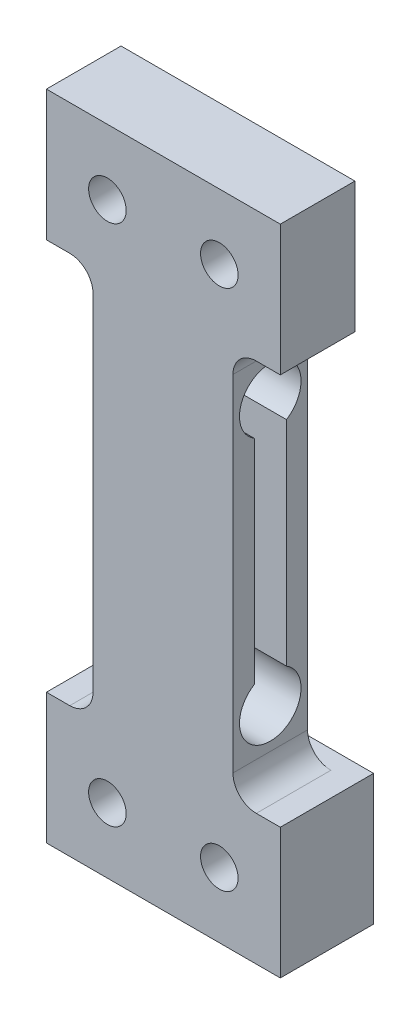
SolidWorks part; units mm, degrees
material "2024 Alloy (SN)"
ref_plane "Front Plane" through (0, 0, 0) normal (0, 0, 1) x (1, 0, 0)
ref_plane "Top Plane" through (0, 0, 0) normal (0, 1, 0) x (1, 0, 0)
ref_plane "Right Plane" through (0, 0, 0) normal (1, 0, 0) x (0, 0, -1)
ref_plane "Plane1" through (0, 0, 0) normal (0, 0, -1) x (-1, 0, 0)
sketch "Sketch1" plane through (0, 0, 0) normal (0, 0, -1) x (-1, 0, 0)
  line L0 (-2.5384, 35) -> (-2.5384, 0)
  line L1 (-2.5384, 0) -> (10, 0)
  line L2 (10, 0) -> (10, 35)
  line L3 (10, 35) -> (-2.5384, 35)
extrude "Boss-Extrude1" add sketch "Sketch1" against normal blind 4
sketch "Sketch2" plane through (0, 0, 4) normal (0, 0, 1) x (1, 0, 0)
  line L0 (2.5384, 28) -> (0, 28)
  line L1 (0, 28) -> (0, 7)
  line L2 (0, 7) -> (2.5384, 7)
  line L3 (2.5384, 7) -> (2.5384, 28)
extrude "Cut-Extrude1" cut sketch "Sketch2" against normal through all
sketch "Sketch3" plane through (0, 0, 4) normal (0, 0, 1) x (1, 0, 0)
  line L0 (-10, 7) -> (-7.5, 7)
  line L1 (-7.5, 7) -> (-7.5, 28)
  line L2 (-7.5, 28) -> (-10, 28)
  line L3 (-10, 28) -> (-10, 7)
extrude "Cut-Extrude2" cut sketch "Sketch3" against normal through all
sketch "Sketch4" plane through (0, 0, 0) normal (1, 0, 0) x (0, 0, -1)
  line L0 (-2.8559, 23.2144) -> (-2.8559, 11.7856)
  line L1 (-1.1318, 11.7781) -> (-1.1318, 23.2219)
  arc A0 (-1.1318, 23.2219) -> (-2.8559, 23.2144) centre (-2, 24.625) cw
  arc A1 (-2.8559, 11.7856) -> (-1.1318, 11.7781) centre (-2, 10.375) cw
extrude "Cut-Extrude3" cut sketch "Sketch4" against normal through all
ref_plane "Plane2" through (0, 0, 2) normal (0, 0, 1) x (1, 0, 0)
sketch "Sketch5" plane through (0, 0, 2) normal (0, 0, 1) x (1, 0, 0)
  line L0 (-7.5, 12.025) -> (-7.5, 10.375)
  line L1 (-7.5, 10.375) -> (0, 10.375)
  line L2 (0, 10.375) -> (0, 12.025)
  line L3 (0, 12.025) -> (-7.5, 12.025)
  line L4 (-7.5, 10.375) -> (0, 10.375) construction
revolve "Cut-Revolve1" cut sketch "Sketch5" angle 360 about L4
sketch "Sketch6" plane through (0, 0, 2) normal (0, 0, 1) x (1, 0, 0)
  line L0 (-7.5, 26.275) -> (-7.5, 24.625)
  line L1 (-7.5, 24.625) -> (0, 24.625)
  line L2 (0, 24.625) -> (0, 26.275)
  line L3 (0, 26.275) -> (-7.5, 26.275)
  line L4 (-7.5, 24.625) -> (0, 24.625) construction
revolve "Cut-Revolve2" cut sketch "Sketch6" angle 360 about L4
hole_wizard "Hole1" positions "Sketch8" profile "Sketch7" legacy
sketch "Sketch8" plane through (0, 0, 0) normal (0, 0, -1) x (-1, 0, 0)
  point P0 (0.7308, 3.5)
  point P1 (6.7308, 3.5)
  point P2 (0.7308, 31.5)
  point P3 (6.7308, 31.5)
sketch "Sketch7" plane through (-0.7308, 3.5, 0) normal (1, 0, 0) x (0, 1, 0)
  line L0 (0, 0) -> (0, 4)
  line L1 (0, 4) -> (1.0065, 4)
  line L2 (1.0065, 4) -> (1.0065, 0)
  line L3 (1.0065, 0) -> (0, 0)
  line L4 (0, 110) -> (0, -10) construction
  dimension "Diameter" = 2.013
  dimension "Depth" = 4
fillet "Fillet1" radius 1.25 4 edges at (0, 28, 2) (0, 7, 2) (-7.5, 28, 2) (-7.5, 7, 2)
sketch "Sketch9" plane through (0, 0, 0) normal (0, 0, -1) x (-1, 0, 0)
  line L1 (-2.5384, 7) -> (10, 7)
  line L2 (-2.5384, 7) -> (-2.5384, 0)
  line L3 (-2.5384, 0) -> (10, 0)
  line L4 (10, 7) -> (10, 0)
extrude "Boss-Extrude2" add sketch "Sketch9" along normal blind 1
